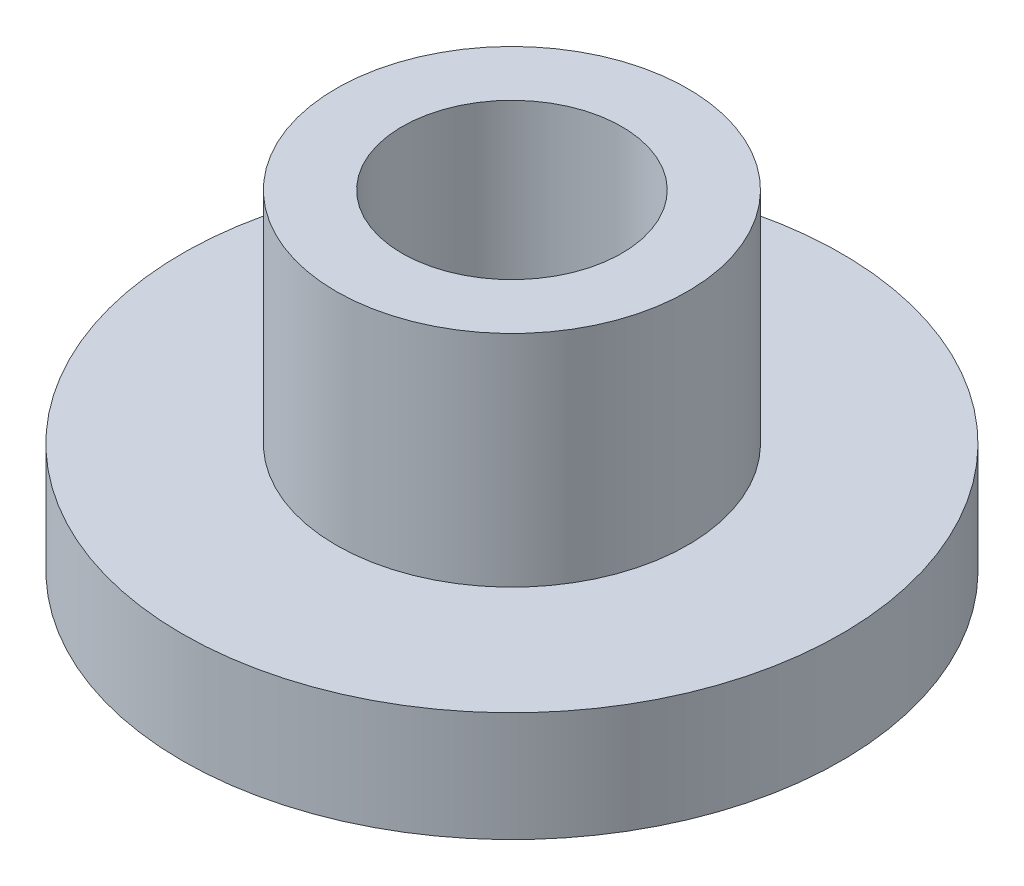
SolidWorks part; units mm, degrees
ref_plane "Plan de face" through (0, 0, 0) normal (0, 0, 1) x (1, 0, 0)
ref_plane "Plan de dessus" through (0, 0, 0) normal (0, 1, 0) x (1, 0, 0)
ref_plane "Plan de droite" through (0, 0, 0) normal (1, 0, 0) x (0, 0, -1)
sketch "Esquisse1" plane through (0, 0, 0) normal (0, 1, 0) x (1, 0, 0)
  circle A0 centre (0, 0) radius 15
  dimension "D1" = 30
extrude "Boss.-Extru.1" add sketch "Esquisse1" along normal blind 5
sketch "Esquisse2" plane through (0, 5, 0) normal (0, 1, 0) x (1, 0, 0)
  circle A0 centre (0, 0) radius 5
  circle A1 centre (0, 0) radius 8
  dimension "D1" = 10
  dimension "D2" = 3
extrude "Boss.-Extru.2" add sketch "Esquisse2" along normal blind 10
